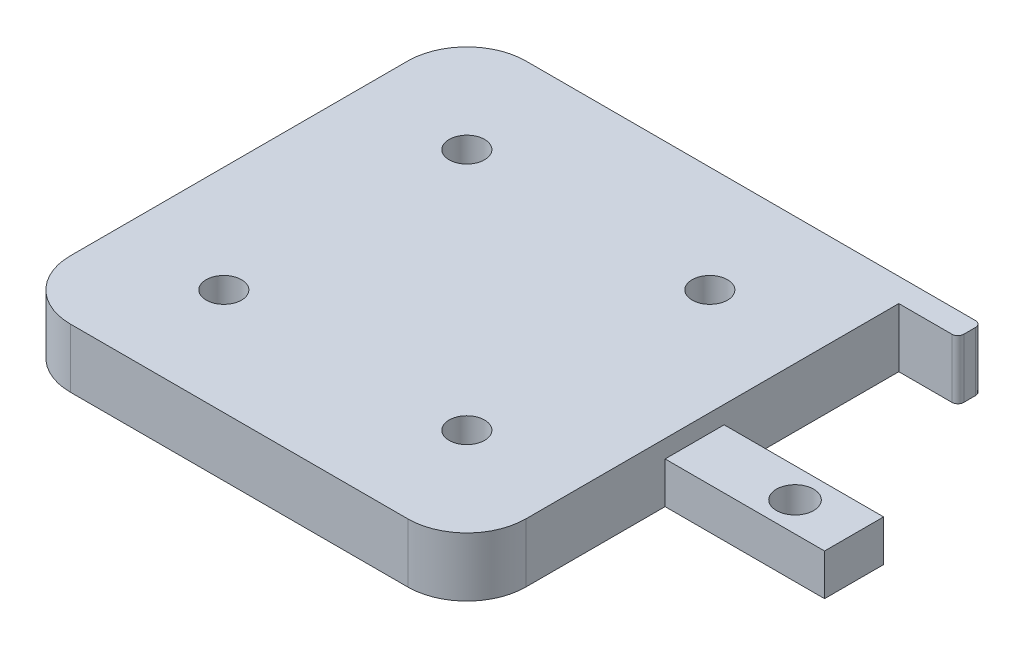
SolidWorks part; units mm, degrees
ref_plane "Front Plane" through (0, 0, 0) normal (0, 0, 1) x (1, 0, 0)
ref_plane "Top Plane" through (0, 0, 0) normal (0, 1, 0) x (1, 0, 0)
ref_plane "Right Plane" through (0, 0, 0) normal (1, 0, 0) x (0, 0, -1)
sketch "Croquis1" plane through (0, 0, 0) normal (0, 1, 0) x (1, 0, 0)
  line L0 (0, 0) -> (-38.575, 0) construction
  line L1 (-38.575, 0) -> (-38.575, 38.575) construction
  line L2 (-38.575, 38.575) -> (38.575, 38.575) construction
  line L3 (38.575, 38.575) -> (38.575, -38.575) construction
  line L4 (38.575, -38.575) -> (-38.575, -38.575) construction
  line L5 (-38.575, -38.575) -> (-38.575, 0) construction
  line L6 (-38.575, 38.575) -> (38.575, 38.575)
  line L7 (38.575, 38.575) -> (38.575, -38.575)
  line L8 (38.575, -38.575) -> (-38.575, -38.575)
  line L9 (-38.575, -38.575) -> (-38.575, 38.575)
  circle A0 centre (-20.575, -20.575) radius 3
  circle A1 centre (-20.575, 20.575) radius 3
  circle A2 centre (20.575, 20.575) radius 3
  circle A3 centre (20.575, -20.575) radius 3
  point P5 (0, -38.575)
  dimension "D4" = 6
  dimension "D8" = 6
  dimension "D11" = 6
  dimension "D13" = 6
  dimension "D1" = 38.575
  dimension "D2" = 38.575
  dimension "D3" = 77.15
  dimension "D5" = 18
  dimension "D6" = 18
  dimension "D7" = 18
  dimension "D9" = 18
  dimension "D10" = 18
  dimension "D12" = 18
  dimension "D14" = 18
  dimension "D15" = 18
extrude "Saliente-Extruir1" add sketch "Croquis1" along normal blind 10
fillet "Redondeo1" radius 10 3 edges at (-38.575, 5, -38.575) (38.575, 5, 38.575) (-38.575, 5, 38.575)
sketch "Croquis2" plane through (38.575, 0, 0) normal (1, 0, 0) x (0, 0, -1)
  line L2 (5, 0) -> (0, 0)
  line L3 (0, 0) -> (-5, 0)
  line L8 (-28.575, 0) -> (38.575, 0) construction
  line L9 (5, 0) -> (5, 7)
  line L10 (5, 7) -> (-5, 7)
  line L11 (-5, 7) -> (-5, 0)
  line L13 (-28.575, 10) -> (-28.575, 0) construction
  dimension "D1" = 5
  dimension "D2" = 5
  dimension "D3" = 0
  dimension "D4" = 7
  dimension "D5" = 23.575
extrude "Saliente-Extruir2" add sketch "Croquis2" along normal blind 30
sketch "Croquis3" plane through (0, 10, 0) normal (0, 1, 0) x (1, 0, 0)
  line L2 (68.575, 5) -> (38.575, 5) construction
  line L3 (68.575, 5) -> (68.575, -5) construction
  circle A0 centre (55.575, 0) radius 3.15
  dimension "D1" = 6.3
  dimension "D2" = 5
  dimension "D3" = 13
extrude "Cortar-Extruir1" cut sketch "Croquis3" against normal blind 5 from surface at -3 contours A0 starting at face at (53.575, 7, 0)
sketch "Croquis4" plane through (0, 10, 0) normal (0, 1, 0) x (1, 0, 0)
  line L0 (65.575, -5) -> (65.575, 5)
  line L3 (65.575, 5) -> (68.575, 5)
  line L4 (68.575, 5) -> (68.575, -5)
  line L5 (68.575, -5) -> (65.575, -5)
  dimension "D1" = 3
extrude "Cortar-Extruir2" cut sketch "Croquis4" against normal blind 43 from surface at -3 starting at face at (55.575, 7, -3.15)
sketch "Croquis5" plane through (38.575, 0, 0) normal (1, 0, 0) x (0, 0, -1)
  line L0 (38.575, 10) -> (34.575, 10)
  line L1 (-28.575, 10) -> (38.575, 10) construction
  line L2 (34.575, 10) -> (34.575, 0)
  line L3 (5, 0) -> (38.575, 0) construction
  line L4 (34.575, 0) -> (38.575, 0)
  line L5 (38.575, 0) -> (38.575, 10)
  dimension "D1" = 4
extrude "Saliente-Extruir3" add sketch "Croquis5" along normal blind 10
fillet "Redondeo2" radius 1 2 edges at (48.575, 5, -34.575) (48.575, 5, -38.575)
